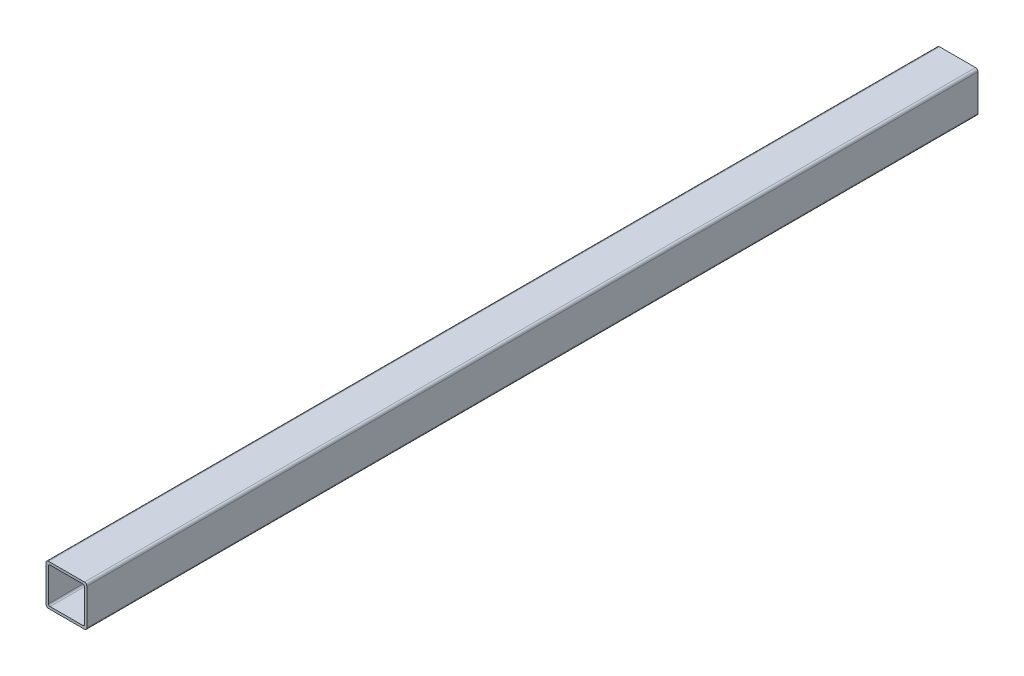
SolidWorks part; units mm, degrees
material "AISI 1020"
ref_plane "Спереди" through (0, 0, 0) normal (0, 0, 1) x (1, 0, 0)
ref_plane "Сверху" through (0, 0, 0) normal (0, 1, 0) x (1, 0, 0)
ref_plane "Справа" through (0, 0, 0) normal (1, 0, 0) x (0, 0, -1)
sketch "Эскиз1" plane through (0, 0, 0) normal (0, 0, 1) x (1, 0, 0)
  line B0 (-22, 25) -> (22, 25)
  line B1 (-25, 22) -> (-25, -22)
  line B2 (-22, -25) -> (22, -25)
  line B3 (25, 22) -> (25, -22)
  line B4 (-20, 22) -> (20, 22)
  line B5 (-22, 20) -> (-22, -20)
  line B6 (-20, -22) -> (20, -22)
  line B7 (22, 20) -> (22, -20)
  arc B8 (-25, -22) -> (-22, -25) centre (-22, -22) ccw
  arc B9 (22, -25) -> (25, -22) centre (22, -22) ccw
  arc B10 (22, 25) -> (25, 22) centre (22, 22) cw
  arc B11 (-22, 25) -> (-25, 22) centre (-22, 22) ccw
  arc B12 (-22, -20) -> (-20, -22) centre (-20, -20) ccw
  arc B13 (20, -22) -> (22, -20) centre (20, -20) ccw
  arc B14 (20, 22) -> (22, 20) centre (20, 20) cw
  arc B15 (-20, 22) -> (-22, 20) centre (-20, 20) ccw
sketch_block_instance "Труба профильная 50х50х3-1"
sketch_block "Труба профильная 50х50х3" parameters "D3"=3, "D4"=2, "D1"=50, "D2"=3
extrude "Бобышка-Вытянуть1" add sketch "Эскиз1" against normal up to surface (1090 mm away)
